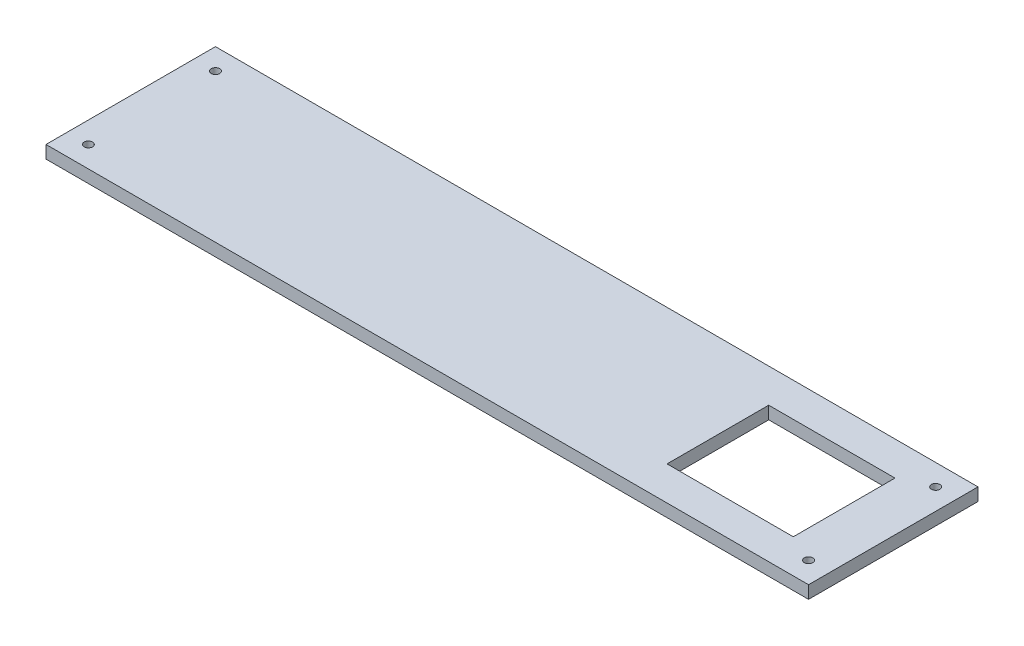
SolidWorks part; units mm, degrees
ref_plane "Front Plane" through (0, 0, 0) normal (0, 0, 1) x (1, 0, 0)
ref_plane "Top Plane" through (0, 0, 0) normal (0, 1, 0) x (1, 0, 0)
ref_plane "Right Plane" through (0, 0, 0) normal (1, 0, 0) x (0, 0, -1)
sketch "Sketch1" plane through (0, 0, 0) normal (0, 1, 0) x (1, 0, 0)
  line L1 (-450, -100) -> (450, -100)
  line L2 (-450, -100) -> (-450, 100)
  line L3 (-450, 100) -> (450, 100)
  line L4 (450, -100) -> (450, 100)
  line L5 (-450, -100) -> (450, 100) construction
  line L6 (-450, 100) -> (450, -100) construction
  line L7 (243, -60) -> (392, -60)
  line L8 (243, -60) -> (243, 60)
  line L9 (243, 60) -> (392, 60)
  line L10 (392, -60) -> (392, 60)
  line L11 (243, -60) -> (392, 60) construction
  line L12 (243, 60) -> (392, -60) construction
  point P0 (0, 0)
  point P5 (317.5, 0)
  dimension "D1" = 58
  dimension "D2" = 120
  dimension "D3" = 200
  dimension "D4" = 900
  dimension "D5" = 149
extrude "Boss-Extrude1" add sketch "Sketch1" along normal blind 15
sketch "Sketch2" plane through (0, 0, 0) normal (0, 1, 0) x (1, 0, 0)
  line L0 (450, 100) -> (-450, 100) construction
  line L1 (-450, 100) -> (-450, -100) construction
  line L2 (-8.25, 0) -> (8.25, 0) construction
  line L3 (0, -8.25) -> (0, 8.25) construction
  circle A0 centre (-425, 75) radius 5
  circle A1 centre (-425, -75) radius 5
  circle A2 centre (425, 75) radius 5
  circle A3 centre (425, -75) radius 5
  dimension "D1" = 10
  dimension "D2" = 25
  dimension "D3" = 25
extrude "Cut-Extrude1" cut sketch "Sketch2" along normal through all
